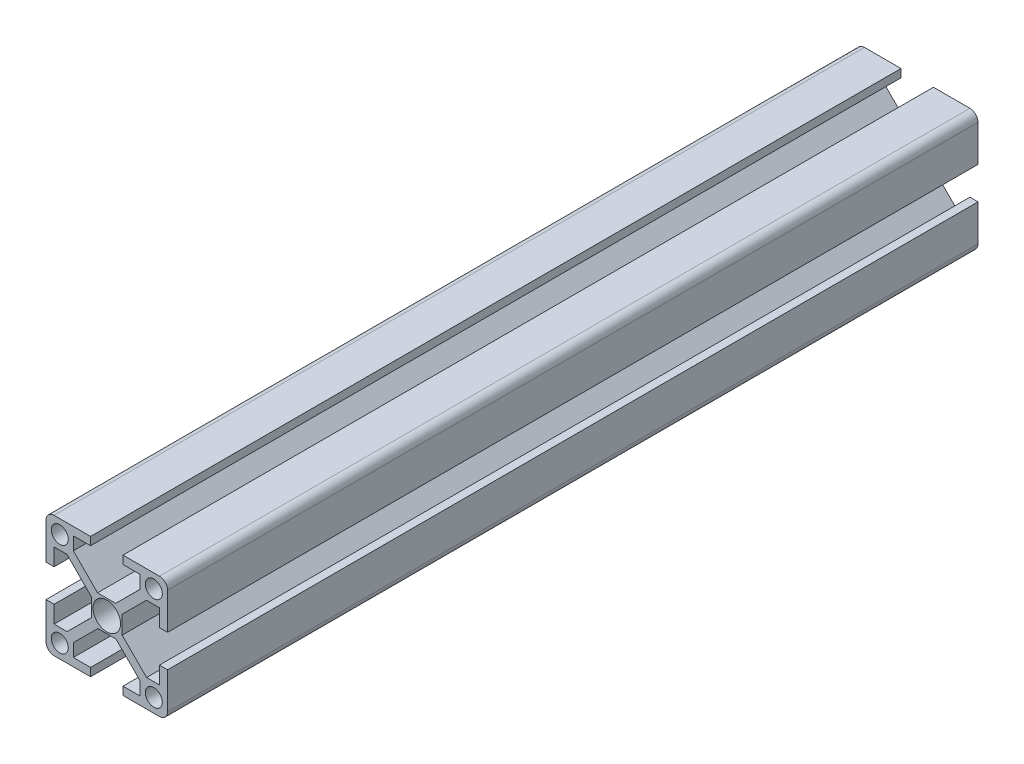
SolidWorks part; units mm, degrees
material "Alumine"
ref_plane "Front Plane" through (0, 0, 0) normal (0, 0, 1) x (1, 0, 0)
ref_plane "Top Plane" through (0, 0, 0) normal (0, 1, 0) x (1, 0, 0)
ref_plane "Right Plane" through (0, 0, 0) normal (1, 0, 0) x (0, 0, -1)
sketch "Sketch1" plane through (0, 0, 0) normal (0, 0, 1) x (1, 0, 0)
  line L0 (-4, 15) -> (-4, -15) construction
  line L1 (15, -15) -> (4, -15)
  line L2 (15, -15) -> (15, -4)
  line L3 (15, 15) -> (4, 15)
  line L4 (-15, -15) -> (-15, -4)
  line L5 (15, -15) -> (-15, 15) construction
  line L6 (15, 15) -> (-15, -15) construction
  line L7 (0, 14.8427) -> (0, -15.1573) construction
  line L8 (4, 15) -> (4, -15) construction
  line L9 (-8.25, 15) -> (-8.25, -15) construction
  line L10 (8.25, 15) -> (8.25, -15) construction
  line L11 (8.25, 13) -> (8.25, 9.8176)
  line L12 (2.2842, -3.8) -> (-2.2044, -3.8)
  line L13 (3.8, -2.2044) -> (3.8, 2.2842)
  line L14 (2.2044, 3.8) -> (-2.2842, 3.8)
  line L15 (-3.8, -2.2842) -> (-3.8, 2.2044)
  line L16 (6.063, -6.0331) -> (-5.6352, 5.6074) construction
  line L17 (5.9365, 6.0624) -> (-5.9369, -6.0628) construction
  line L20 (-13, 8.25) -> (-9.8176, 8.25)
  line L21 (-8.25, 13) -> (-8.25, 9.7936)
  line L22 (-14.8942, 14.9095) -> (-8.21, 8.1942) construction
  line L23 (-14.95, 8.25) -> (-8.25, 14.95) construction
  line L24 (-10.2, 13) -> (-10.0348, 13)
  line L25 (-13, 10.2) -> (-13, 10.0348)
  line L26 (-8.25, -13) -> (-4, -13)
  line L27 (13, 8.25) -> (13, 4)
  line L28 (-13, 13) -> (13, -13) construction
  line L29 (-13, -13) -> (13, 13) construction
  line L30 (13, 8.25) -> (9.7936, 8.25)
  line L31 (13, -8.25) -> (9.8176, -8.25)
  line L32 (8.25, -13) -> (8.25, -9.7936)
  line L33 (-8.25, -13) -> (-8.25, -9.8176)
  line L34 (-13, -8.25) -> (-9.7936, -8.25)
  line L35 (-8.21, 8.1942) -> (-5.6352, 5.6074)
  line L36 (-9.8176, 8.25) -> (-3.8, 2.2044)
  line L37 (-8.25, 9.7936) -> (-2.2842, 3.8)
  line L38 (-8.9896, 7.4182) -> (-6.4149, 4.8314) construction
  line L39 (-7.4304, 8.9702) -> (-4.8556, 6.3834) construction
  line L40 (-4, 15) -> (-4, 13)
  line L41 (4, 15) -> (4, 13)
  line L42 (8.25, 9.8176) -> (2.2044, 3.8)
  line L43 (9.7936, 8.25) -> (3.8, 2.2842)
  line L44 (15, 4) -> (13, 4)
  line L45 (15, -4) -> (13, -4)
  line L46 (9.8176, -8.25) -> (3.8, -2.2044)
  line L47 (8.25, -9.7936) -> (2.2842, -3.8)
  line L48 (4, -15) -> (4, -13)
  line L49 (-4, -15) -> (-4, -13)
  line L50 (-8.25, -9.8176) -> (-2.2044, -3.8)
  line L51 (-9.7936, -8.25) -> (-3.8, -2.2842)
  line L52 (-15, -4) -> (-13, -4)
  line L53 (-15, 4) -> (-13, 4)
  line L54 (-15, 4) -> (-15, 15)
  line L55 (-13, -4) -> (-13, -8.25)
  line L56 (4, 13) -> (8.25, 13)
  line L57 (-4, 15) -> (-15, 15)
  line L58 (13, -4) -> (13, -8.25)
  line L59 (15, 4) -> (15, 15)
  line L60 (-8.25, 13) -> (-4, 13)
  line L61 (-13, 8.25) -> (-13, 4)
  line L62 (4, -13) -> (8.25, -13)
  line L63 (-4, -15) -> (-15, -15)
  circle A0 centre (0, 0) radius 3.4
  circle A1 centre (-11.6, 11.6) radius 2.1
  circle A2 centre (11.6, 11.6) radius 2.1
  circle A3 centre (11.6, -11.6) radius 2.1
  circle A4 centre (-11.6, -11.6) radius 2.1
  point P0 (0, 0)
  point P19 (-11.6, 15)
  point P52 (0, 0)
  point P87 (0, 0)
  dimension "D3" = 6.8
  dimension "D9" = 4.2
  dimension "D1" = 30
  dimension "D2" = 30
  dimension "D4" = 11
  dimension "D5" = 8.25
  dimension "D6" = 11.6
  dimension "D7" = 3.4
  dimension "D8" = 3.4
  dimension "D10" = 12
  dimension "D11" = 2
  dimension "D16" = 9.2
  dimension "D13" = 1.1
  dimension "D14" = 1.1
  dimension "D12" = 4
  dimension "D15" = 4
extrude "Boss-Extrude1" add sketch "Sketch1" along normal blind 200
fillet "Fillet1" radius 2 4 edges at (-15, -15, 100) (15, -15, 100) (-15, 15, 100) (15, 15, 100)
ref_plane "Plane1" through (0, 0, 0) normal (1, 0, 0) x (0, 0, -1)
